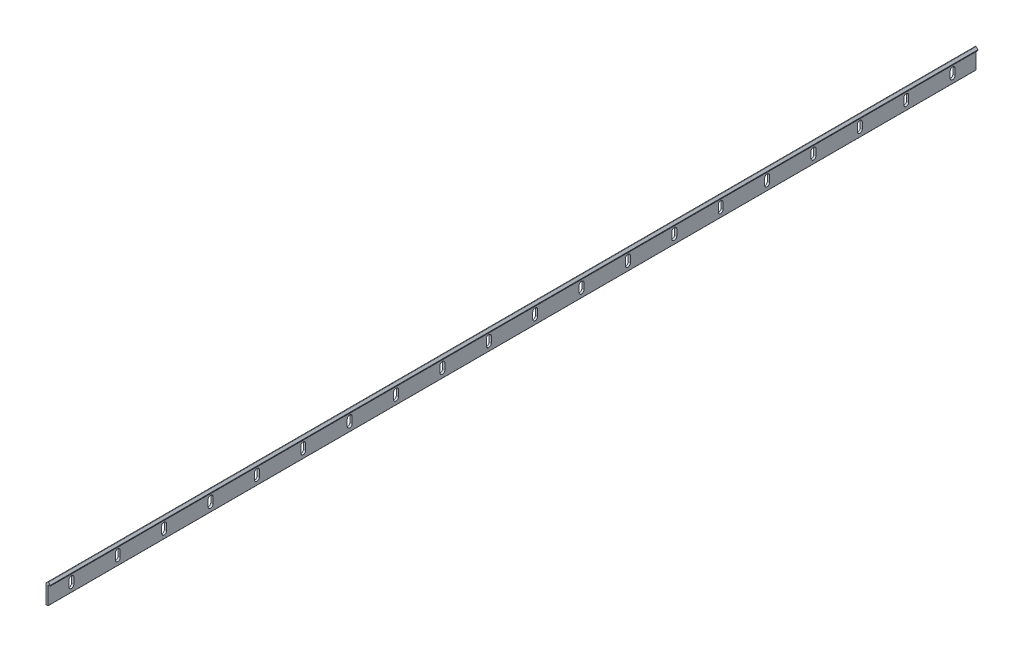
SolidWorks part; units mm, degrees
ref_plane "Front Plane" through (0, 0, 0) normal (0, 0, 1) x (1, 0, 0)
ref_plane "Top Plane" through (0, 0, 0) normal (0, 1, 0) x (1, 0, 0)
ref_plane "Right Plane" through (0, 0, 0) normal (1, 0, 0) x (0, 0, -1)
sketch "Sketch1" plane through (0, 0, 0) normal (0, 0, 1) x (1, 0, 0)
  line L0 (0, 20.3302) -> (2.0196, 22.3498)
  line L1 (0, 0) -> (2.375, 0)
  line L2 (0, 20.3302) -> (0, 0)
  line L4 (2.375, 0) -> (2.375, 19.5291)
  line L5 (2.375, 19.5291) -> (4.75, 19.5291)
  line L7 (2.7304, 22.3498) -> (4.75, 20.3302)
  line L8 (4.75, 19.5291) -> (4.75, 20.3302)
  arc A0 (2.7304, 22.3498) -> (2.0196, 22.3498) centre (2.375, 21.9944) ccw
  point P9 (2.375, 22.7052)
  dimension "D5" = 0.5026
  dimension "D6" = 22.497
  dimension "D1" = 2.375
  dimension "D2" = 19.5291
  dimension "D3" = 2.375
  dimension "D4" = 2.9679
extrude "Boss-Extrude1" add sketch "Sketch1" along normal blind 1000
fillet "Fillet1" radius 0.5033 1 edges at (0, 20.3302, 500)
fillet "Fillet2" radius 0.504 1 edges at (4.75, 20.3302, 500)
fillet "Fillet3" radius 0.3016 1 edges at (4.75, 19.5291, 500)
fillet "Fillet4" radius 0.3016 2 edges at (0, 0, 500) (2.375, 0, 500)
sketch "Sketch2" plane through (0, 0, 0) normal (-1, 0, 0) x (0, 0, 1)
  line L0 (25, 13.1043) -> (25, 6.4043) construction
  line L1 (27.65, 13.1043) -> (27.65, 6.4043)
  line L2 (22.35, 13.1043) -> (22.35, 6.4043)
  line L3 (1000, 0) -> (0, 0) construction
  line L4 (0, 20.1217) -> (0, 0.3016) construction
  arc A0 (27.65, 13.1043) -> (22.35, 13.1043) centre (25, 13.1043) ccw
  arc A1 (22.35, 6.4043) -> (27.65, 6.4043) centre (25, 6.4043) ccw
  point P2 (25, 9.7543)
  dimension "D3" = 9.7543
  dimension "D1" = 5.3
  dimension "D2" = 6.7
  dimension "D4" = 25
extrude "Cut-Extrude1" cut sketch "Sketch2" against normal up to next
pattern_linear "LPattern1" count 20 spacing 50 along (0, 0, 1) of "Cut-Extrude1"
equation "\"D3@Sketch1\"=\"D1@Sketch1\""
